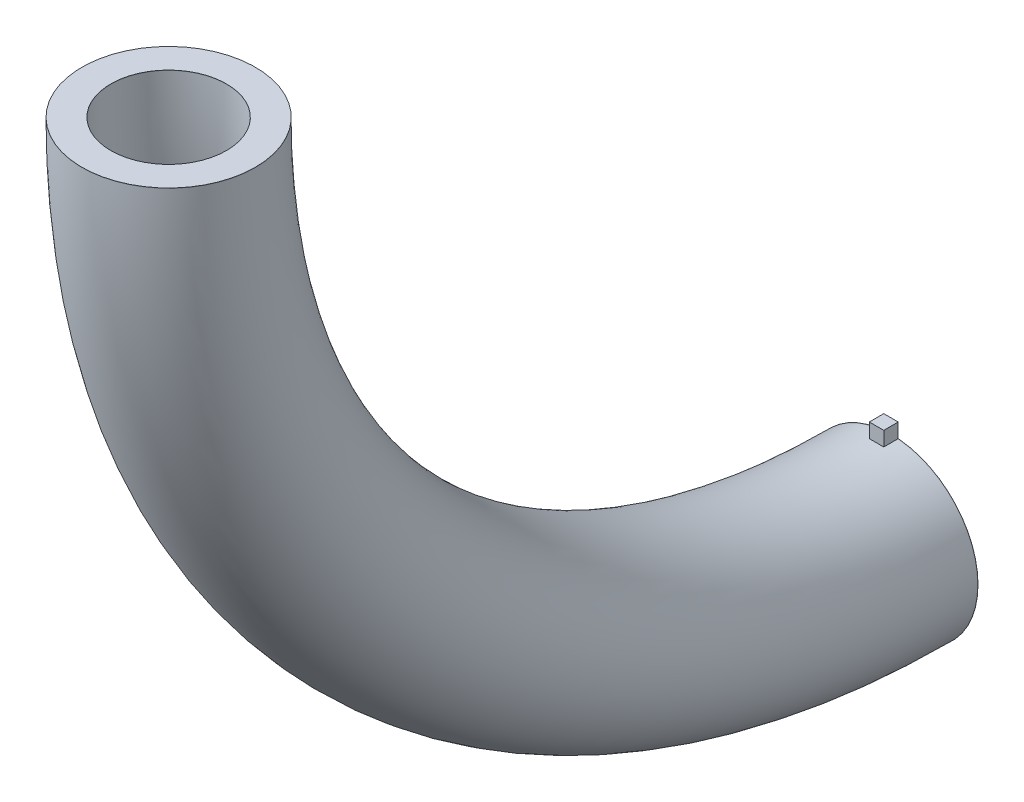
SolidWorks part; units mm, degrees
ref_plane "Front Plane" through (0, 0, 0) normal (0, 0, 1) x (1, 0, 0)
ref_plane "Top Plane" through (0, 0, 0) normal (0, 1, 0) x (1, 0, 0)
ref_plane "Right Plane" through (0, 0, 0) normal (1, 0, 0) x (0, 0, -1)
sketch "Sketch1" plane through (0, 0, 0) normal (0, 0, 1) x (1, 0, 0)
  circle A0 centre (0, 0) radius 3
  circle A1 centre (0, 0) radius 2
  dimension "D1" = 6
  dimension "D2" = 1
sketch "Sketch2" plane through (0, 0, 0) normal (1, 0, 0) x (0, 0, -1)
  line L0 (0, 0) -> (-0.01, 0)
  line L1 (-25, 24.99) -> (-25, 25)
  arc A0 (-0.01, 0) -> (-25, 24.99) centre (-0.01, 24.99) cw
  point P6 (-25, 0)
  dimension "D3" = 24.99
  dimension "D1" = 25
  dimension "D2" = 25
sweep "Sweep1" add profiles "Sketch1" path "Sketch2"
sketch "Sketch3" plane through (0, 0, 0) normal (1, 0, 0) x (0, 0, -1)
  line L1 (-0.01, 3) -> (-0.51, 3)
  line L2 (-0.01, 3) -> (-0.01, 3.5)
  line L3 (-0.01, 3.5) -> (-0.51, 3.5)
  line L4 (-0.51, 3) -> (-0.51, 3.5)
  dimension "D1" = 0.5
  dimension "D2" = 0.5
extrude "Boss-Extrude1" add sketch "Sketch3" along normal mid plane 0.5
